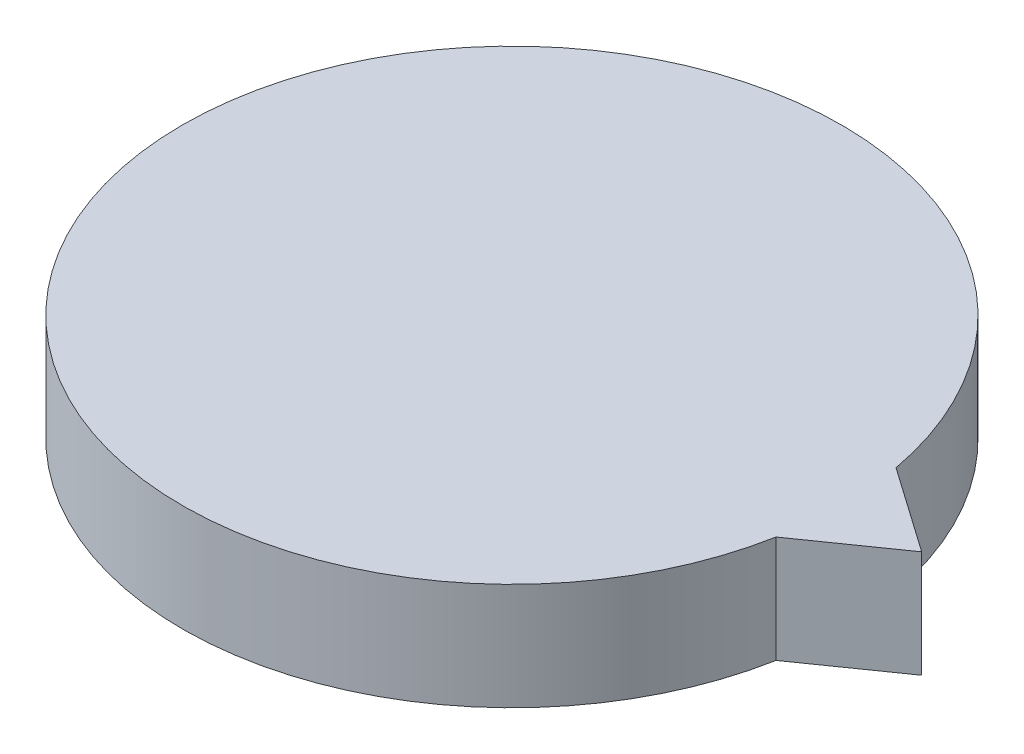
SolidWorks part; units mm, degrees
ref_plane "Front" through (0, 0, 0) normal (0, 0, 1) x (1, 0, 0)
ref_plane "Top" through (0, 0, 0) normal (0, 1, 0) x (1, 0, 0)
ref_plane "Right" through (0, 0, 0) normal (1, 0, 0) x (0, 0, -1)
sketch "Sketch2" plane through (0, 0, 0) normal (0, 1, 0) x (1, 0, 0)
  circle A0 centre (0, 0) radius 18.5
extrude "Boss-Extrude1" add sketch "Sketch2" along normal blind 3
sketch "Sketch3" plane through (0, 0, 0) normal (0, -1, 0) x (1, 0, 0)
  circle A0 centre (0, 0) radius 18.5
  circle A1 centre (0, 0) radius 16.5
extrude "Boss-Extrude2" add sketch "Sketch3" along normal blind 3
sketch "Sketch4" plane through (0, 3, 0) normal (0, 1, 0) x (1, 0, 0)
  circle A0 centre (0, 0) radius 3.25
  circle A1 centre (0, 0) radius 5.9
extrude "Boss-Extrude3" add sketch "Sketch4" against normal blind 5
sketch "Sketch5" plane through (0, 0, 0) normal (0, -1, 0) x (1, 0, 0)
  line L0 (4.5967, 3.7127) -> (1.2848, 1.0377)
  line L1 (1.4438, -0.5563) -> (5.5137, -2.1245)
  line L2 (-0.7667, -0.6193) -> (-4.5967, -3.7127)
  line L3 (0.9169, -5.8373) -> (0.1504, -0.9576)
  line L4 (-0.2094, 1.3329) -> (-0.9169, 5.8373)
  line L5 (-5.5137, 2.1245) -> (-1.089, 0.4196)
  line L7 (-0.2094, 1.3329) -> (-1.089, 0.4196)
  line L9 (1.2848, 1.0377) -> (1.4438, -0.5563)
  line L11 (0.1504, -0.9576) -> (-0.7667, -0.6193)
  arc A0 (4.5967, 3.7127) -> (5.5137, -2.1245) centre (0, 0) cw
  arc A1 (0.9169, -5.8373) -> (-4.5967, -3.7127) centre (0, 0) cw
  arc A2 (-5.5137, 2.1245) -> (-0.9169, 5.8373) centre (0, 0) cw
  point P11 (0, 0)
  dimension "D1" = 3
extrude "Cut-Extrude2" cut sketch "Sketch5" along normal blind 5
sketch "Sketch6" plane through (0, 3, 0) normal (0, 1, 0) x (1, 0, 0)
  line L0 (18.191, 3.3673) -> (18.191, -3.3673)
  line L1 (23, 0) -> (18.191, -3.3673)
  line L3 (18.191, 3.3673) -> (23, 0)
  circle A0 centre (0, 0) radius 18.5 construction
extrude "Boss-Extrude4" add sketch "Sketch6" against normal up to surface (6 mm away) up to face at (0, -3, -18.5)
